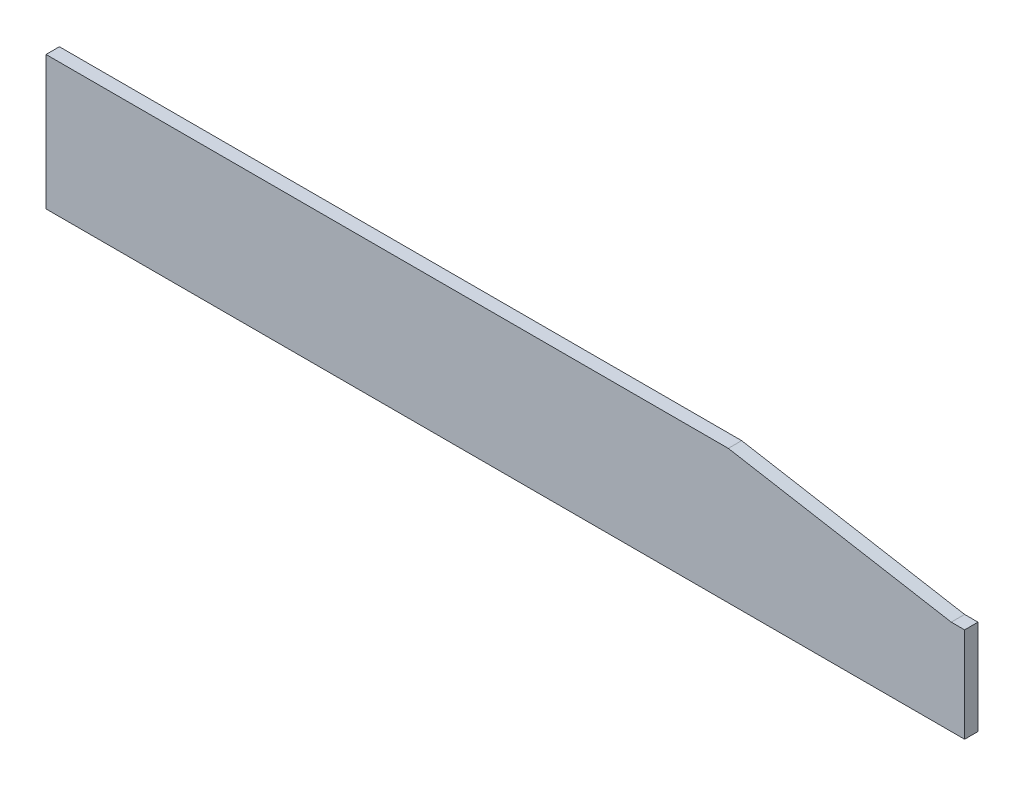
SolidWorks part; units mm, degrees
material "CA"
ref_plane "Front Plane" through (0, 0, 0) normal (0, 0, 1) x (1, 0, 0)
ref_plane "Top Plane" through (0, 0, 0) normal (0, 1, 0) x (1, 0, 0)
ref_plane "Right Plane" through (0, 0, 0) normal (1, 0, 0) x (0, 0, -1)
sketch "Sketch1" plane through (0, 0, 0) normal (0, 0, 1) x (1, 0, 0)
  line L0 (-83.6552, 53.3781) -> (-83.6552, -6.6219)
  line L1 (-83.6552, -6.6219) -> (328.3448, -6.6219)
  line L3 (222.3448, 53.3781) -> (-83.6552, 53.3781)
  line L5 (328.3448, -6.6219) -> (328.3448, 35.8781)
  line L6 (328.3448, 35.8781) -> (322.3448, 35.8781)
  line L7 (322.3448, 35.8781) -> (222.3448, 53.3781)
  dimension "D1" = 306
  dimension "D2" = 60
  dimension "D3" = 42.5
  dimension "D4" = 412
  dimension "D5" = 101.5197
extrude "Boss-Extrude1" add sketch "Sketch1" along normal blind 6
